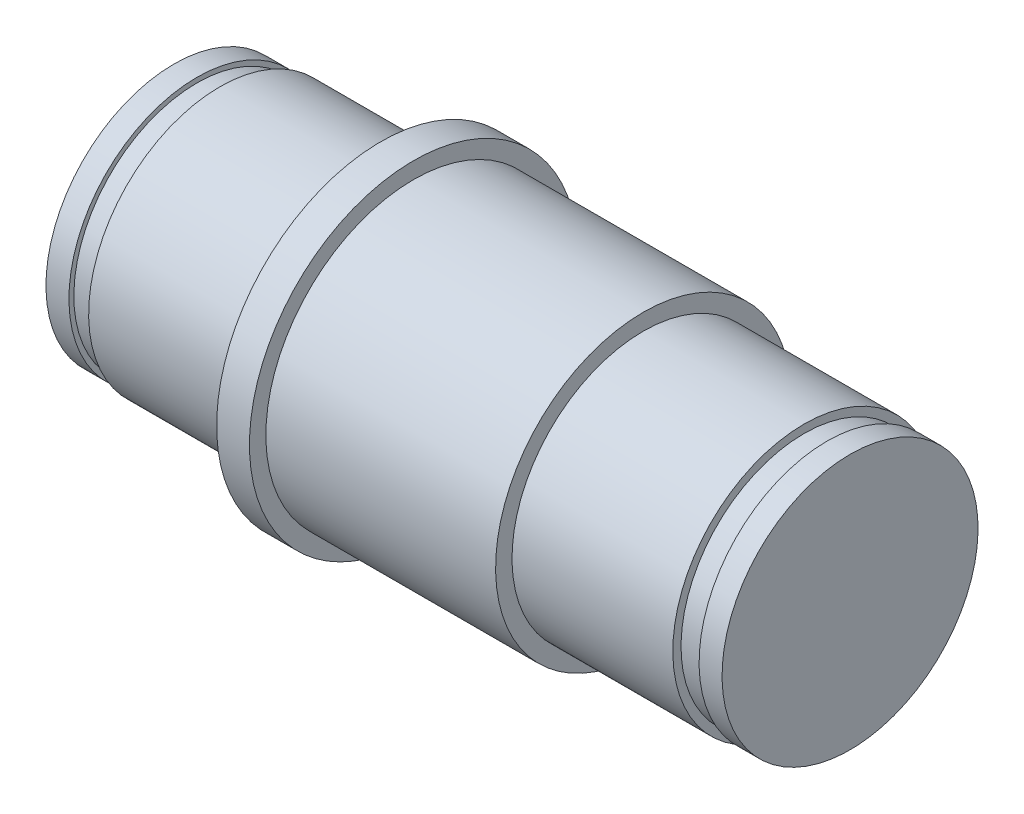
SolidWorks part; units mm, degrees
material "5052-H32"
ref_plane "Front Plane" through (0, 0, 0) normal (0, 0, 1) x (1, 0, 0)
ref_plane "Top Plane" through (0, 0, 0) normal (0, 1, 0) x (1, 0, 0)
ref_plane "Right Plane" through (0, 0, 0) normal (1, 0, 0) x (0, 0, -1)
sketch "Sketch1" plane through (0, 0, 0) normal (0, 0, 1) x (1, 0, 0)
  line L0 (10.3, 0) -> (-10.3, 0)
  line L1 (-10.3, 0) -> (-10.3, 3.9)
  line L2 (-10.3, 3.9) -> (-9.6, 3.9)
  line L3 (-9.6, 3.9) -> (-9.6, 3.75)
  line L4 (-9.6, 3.75) -> (-8.9, 3.75)
  line L5 (-8.9, 3.75) -> (-8.9, 4)
  line L6 (-8.9, 4) -> (-4, 4)
  line L7 (-4, 4) -> (-4, 4.5)
  line L8 (-4, 4.5) -> (4, 4.5)
  line L9 (4, 4.5) -> (4, 4)
  line L10 (4, 4) -> (8.9, 4)
  line L11 (8.9, 4) -> (8.9, 3.75)
  line L12 (8.9, 3.75) -> (9.6, 3.75)
  line L13 (9.6, 3.75) -> (9.6, 3.9)
  line L14 (9.6, 3.9) -> (10.3, 3.9)
  line L15 (10.3, 3.9) -> (10.3, 0)
  line L16 (15.6918, 0) -> (-16.7203, 0) construction
revolve "Revolve1" add sketch "Sketch1" angle 360 about L16
sketch "Sketch2" plane through (0, 0, 0) normal (1, 0, 0) x (0, 0, -1)
  line L0 (4.0311, 2) -> (4.0311, -2)
  arc A0 (4.0311, -2) -> (4.0311, 2) centre (0, 0) ccw
  circle A1 centre (0, 0) radius 4.5 construction
extrude "Cut-Extrude1" [suppressed] cut sketch "Sketch2" against normal up to vertex and the other way up to vertex
sketch "Sketch3" plane through (0, 0, 0) normal (0, 0, 1) x (1, 0, 0)
  line L0 (-4, 5) -> (-4, 4.5)
  line L1 (-4, 4.5) -> (-3, 4.5)
  line L2 (-3, 4.5) -> (-3, 5)
  line L3 (-3, 5) -> (-4, 5)
  line L4 (0, 0) -> (-0.8134, 0) construction
revolve "Revolve2" add sketch "Sketch3" angle 360 about L4
